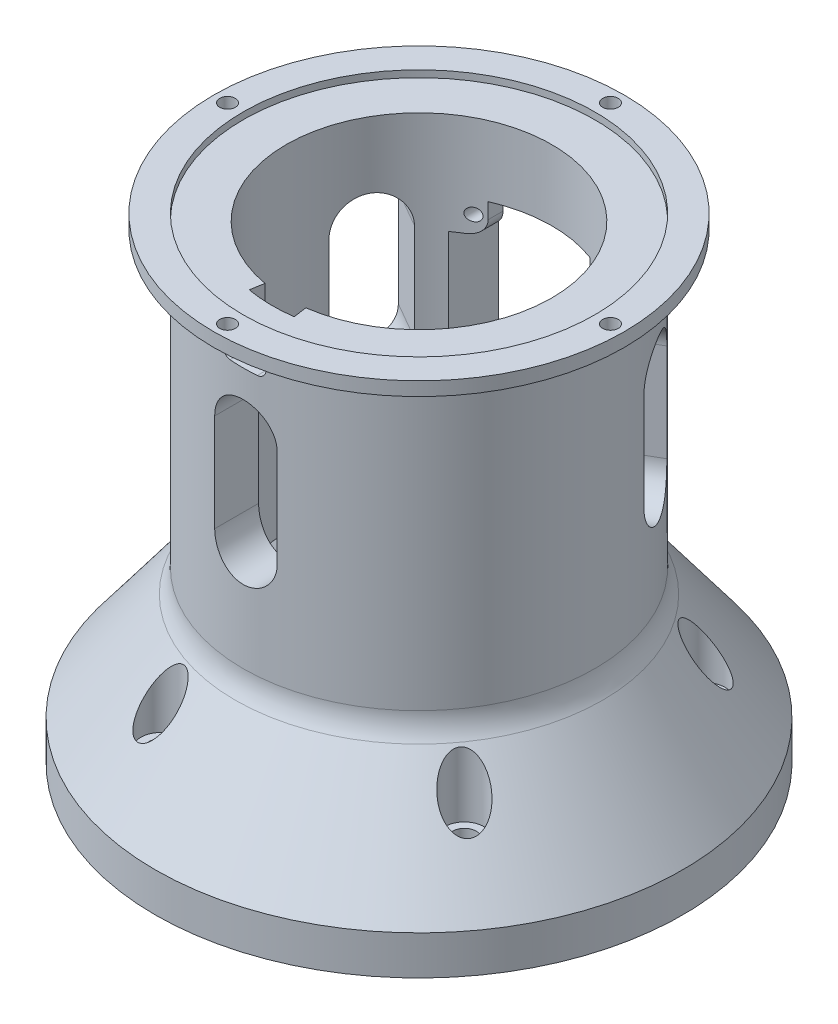
SolidWorks part; units mm, degrees
ref_plane "Front Plane" through (0, 0, 0) normal (0, 0, 1) x (1, 0, 0)
ref_plane "Top Plane" through (0, 0, 0) normal (0, 1, 0) x (1, 0, 0)
ref_plane "Right Plane" through (0, 0, 0) normal (1, 0, 0) x (0, 0, -1)
sketch "Sketch1" plane through (0, 0, 0) normal (0, 1, 0) x (1, 0, 0)
  circle A0 centre (0, 0) radius 67.5
  dimension "D1" = 135
ref_plane "Plane1" through (0, 30, 0) normal (0, 1, 0) x (1, 0, 0)
sketch "Sketch2" plane through (0, 30, 0) normal (0, 1, 0) x (1, 0, 0)
  circle A0 centre (0, 0) radius 45
  dimension "D1" = 90
loft "Loft1" add profiles "Sketch1", "Sketch2"
sketch "Sketch4" plane through (0, 30, 0) normal (0, 1, 0) x (1, 0, 0)
  circle A0 centre (0, 0) radius 52.5 construction
  circle A1 centre (-52.5, 0) radius 3
  circle A2 centre (-16.2234, 49.9305) radius 3
  circle A3 centre (42.4734, 30.8587) radius 3
  circle A4 centre (42.4734, -30.8587) radius 3
  circle A5 centre (-16.2234, -49.9305) radius 3
  point P15 (0, 0)
  dimension "D1" = 105
  dimension "D2" = 6
  dimension "D3" = 5
extrude "Cut-Extrude2" cut sketch "Sketch4" against normal through all
sketch "Sketch5" plane through (0, 30, 0) normal (0, 1, 0) x (1, 0, 0)
  circle A0 centre (-52.5, 0) radius 3 construction
  circle A1 centre (-52.5, 0) radius 3
  circle A2 centre (-52.5, 0) radius 5
  circle A3 centre (-16.2234, 49.9305) radius 5
  circle A4 centre (42.4734, 30.8587) radius 5
  circle A5 centre (42.4734, -30.8587) radius 5
  circle A6 centre (-16.2234, -49.9305) radius 5
  point P14 (0, 0)
  dimension "D1" = 10
  dimension "D3" = 52.5
  dimension "D2" = 5
extrude "Cut-Extrude3" cut sketch "Sketch5" against normal blind 20
sketch "Sketch6" plane through (0, 30, 0) normal (0, 1, 0) x (1, 0, 0)
  circle A1 centre (0, 0) radius 45
  circle A2 centre (0, 0) radius 45
  dimension "D1" = 0
extrude "Boss-Extrude1" add sketch "Sketch6" along normal blind 80
fillet "Fillet1" radius 10 1 edges at (0, 30, 45)
sketch "Sketch11" plane through (17.444, 57.5446, 0) normal (0, 0, 1) x (1, 0, 0)
  line L0 (-17.444, 52.4554) -> (-51.444, 52.4554)
  line L1 (27.556, 52.4554) -> (-62.444, 52.4554) construction
  line L2 (-51.444, 52.4554) -> (-51.444, -33.5446)
  line L5 (-51.444, -33.5446) -> (-40.444, -43.7852)
  line L8 (-40.444, -43.7852) -> (-17.444, -43.7852)
  line L9 (-17.444, 52.4554) -> (-17.444, -43.7852)
  dimension "D1" = 34
  dimension "D2" = 137.047
  dimension "D3" = 23
  dimension "D4" = 86
revolve "Cut-Revolve1" cut sketch "Sketch11" angle 360 about L9
sketch "Sketch12" plane through (0, 0, 0) normal (0, -1, 0) x (1, 0, 0)
  circle A1 centre (0, 0) radius 67.5
  circle A2 centre (0, 0) radius 67.5
  dimension "D1" = 0
extrude "Boss-Extrude2" add sketch "Sketch12" along normal blind 10
sketch "Sketch15" plane through (0, -10, 0) normal (0, -1, 0) x (1, 0, 0)
  circle A0 centre (42.4734, 30.8587) radius 3 construction
  circle A3 centre (-52.5, 0) radius 3
  circle A4 centre (-52.5, 0) radius 3
  circle A5 centre (42.4734, -30.8587) radius 3 construction
  circle A6 centre (-16.2234, -49.9305) radius 3 construction
  circle A7 centre (-16.2234, 49.9305) radius 3 construction
  circle A8 centre (42.4734, 30.8587) radius 3
  circle A9 centre (42.4734, -30.8587) radius 3
  circle A10 centre (-16.2234, -49.9305) radius 3
  circle A11 centre (-16.2234, 49.9305) radius 3
  dimension "D2" = 0
extrude "Cut-Extrude5" cut sketch "Sketch15" against normal blind 20
sketch "Sketch16" plane through (0, 0, 0) normal (0, 0, 1) x (1, 0, 0)
  line L0 (0, 85) -> (0, 60) construction
  line L1 (8, 85) -> (8, 60)
  line L2 (-8, 85) -> (-8, 60)
  arc A0 (8, 85) -> (-8, 85) centre (0, 85) ccw
  arc A1 (-8, 60) -> (8, 60) centre (0, 60) ccw
  point P3 (0, 72.5)
  dimension "D3" = 8
  dimension "D1" = 60
  dimension "D2" = 25
extrude "Cut-Extrude6" cut sketch "Sketch16" along normal blind 50
pattern_circular "CirPattern1" count 3 every 120 about axis through (0, 0, 0) along (0, 1, 0) of "Cut-Extrude6"
sketch "Sketch18" plane through (0, 0, 0) normal (0, 0, 1) x (1, 0, 0)
  line L0 (0, 0) -> (0, 72.5) construction
  line L1 (16, 85.5) -> (20, 85.5)
  line L2 (12, 92) -> (-13.5, 92)
  line L3 (20, 85.5) -> (20, 60)
  line L4 (13.5, 52) -> (-12, 52)
  line L5 (-20, 84) -> (-20, 58.5)
  line L6 (13.7161, 86.2161) -> (-14.3542, 58.1458) construction
  line L8 (12, 89.5) -> (12, 92)
  line L9 (13.5, 56) -> (13.5, 52)
  line L10 (17.5, 60) -> (20, 60)
  line L11 (-16, 58.5) -> (-20, 58.5)
  line L12 (-12, 54.5) -> (-12, 52)
  line L13 (-13.5, 88) -> (-13.5, 92)
  line L14 (-17.5, 84) -> (-20, 84)
  line L17 (13.6021, 56.8979) -> (-14.6716, 85.1716) construction
  arc A5 (12, 89.5) -> (16, 85.5) centre (16, 89.5) ccw
  arc A6 (17.5, 60) -> (13.5, 56) centre (17.5, 56) ccw
  arc A7 (-12, 54.5) -> (-16, 58.5) centre (-16, 54.5) ccw
  arc A8 (-17.5, 84) -> (-13.5, 88) centre (-17.5, 88) ccw
  point P39 (0, 72)
  dimension "D4" = 4
  dimension "D3" = 40
  dimension "D1" = 72.5
  dimension "D2" = 4
extrude "Cut-Extrude7" cut sketch "Sketch18" against normal blind 50
ref_plane "Plane2" through (0, 0, -60) normal (0, 0, 1) x (1, 0, 0)
sketch "Sketch22" plane through (0, 0, -60) normal (0, 0, 1) x (1, 0, 0)
  line L0 (0, 0) -> (0, 72.5) construction
  line L1 (-67.5, 0) -> (67.5, 0) construction
  line L3 (20, 92.5) -> (-20, 92.5)
  line L4 (20, 92.5) -> (20, 52.5)
  line L5 (20, 52.5) -> (-20, 52.5)
  line L6 (-20, 92.5) -> (-20, 52.5)
  line L7 (20, 92.5) -> (-20, 52.5) construction
  line L8 (20, 52.5) -> (-20, 92.5) construction
  dimension "D1" = 72.5
  dimension "D2" = 40
  dimension "D3" = 40
extrude "Cut-Extrude8" cut sketch "Sketch22" along normal blind 25
sketch "Sketch23" plane through (0, 0, -60) normal (0, 0, 1) x (1, 0, 0)
  line L0 (0, 0) -> (0, 72.5) construction
  line L1 (0, 72.5) -> (-5.5729, 72.5) construction
  line L2 (20, 92.5) -> (-20, 92.5) construction
  line L3 (20, 92.5) -> (20, 52.5) construction
  line L4 (20, 52.5) -> (-20, 52.5) construction
  line L5 (-20, 92.5) -> (-20, 52.5) construction
  circle A0 centre (16, 88.5) radius 1.6
  circle A4 centre (-16, 88.5) radius 1.6
  circle A5 centre (-16, 56.5) radius 1.6
  circle A6 centre (16, 56.5) radius 1.6
  dimension "D3" = 3.2
  dimension "D5" = 16
  dimension "D1" = 72.5
  dimension "D2" = 40
  dimension "D4" = 16
extrude "Cut-Extrude9" cut sketch "Sketch23" along normal blind 36
sketch "Sketch30" plane through (0, 0, 0) normal (0, 0, 1) x (1, 0, 0)
  line L0 (-3.5, 102) -> (3.5, 102) construction
  line L1 (-3.5, 104) -> (3.5, 104)
  line L2 (-3.5, 100) -> (3.5, 100)
  arc A0 (-3.5, 104) -> (-3.5, 100) centre (-3.5, 102) ccw
  arc A1 (3.5, 100) -> (3.5, 104) centre (3.5, 102) ccw
  point P2 (0, 102)
  dimension "D3" = 2
  dimension "D1" = 102
  dimension "D2" = 7
extrude "Cut-Extrude12" cut sketch "Sketch30" along normal blind 70
sketch "Sketch32" plane through (0, 110, 0) normal (0, 1, 0) x (1, 0, 0)
  line L0 (4.7093, -33.6723) -> (5.1941, -37.1385)
  line L1 (-5.9265, -33.4795) -> (-6.5365, -36.9259)
  circle A0 centre (0, 0) radius 34 construction
  arc A1 (-5.9265, -33.4795) -> (4.7093, -33.6723) centre (0, 0) ccw
  arc A2 (-6.5365, -36.9259) -> (5.1941, -37.1385) centre (0, 0) ccw
  dimension "D1" = 75
  dimension "D2" = 18
extrude "Cut-Extrude14" cut sketch "Sketch32" against normal up to surface (6 mm away) up to face at (0, 104, 39.4208)
sketch "Sketch33" plane through (0, 110, 0) normal (0, 1, 0) x (1, 0, 0)
  circle A0 centre (0, 0) radius 52.5
  circle A1 centre (0, 0) radius 45 construction
  circle A2 centre (0, 0) radius 45
  dimension "D1" = 105
extrude "Boss-Extrude3" add sketch "Sketch33" against normal mid plane 3.5
sketch "Sketch34" plane through (0, 111.75, 0) normal (0, 1, 0) x (1, 0, 0)
  circle A0 centre (0, 0) radius 49 construction
  circle A1 centre (0, 49) radius 2
  circle A2 centre (49, 0) radius 2
  circle A3 centre (0, -49) radius 2
  circle A4 centre (-49, 0) radius 2
  point P14 (0, 0)
  dimension "D1" = 98
  dimension "D2" = 4
extrude "Cut-Extrude15" cut sketch "Sketch34" against normal blind 10
